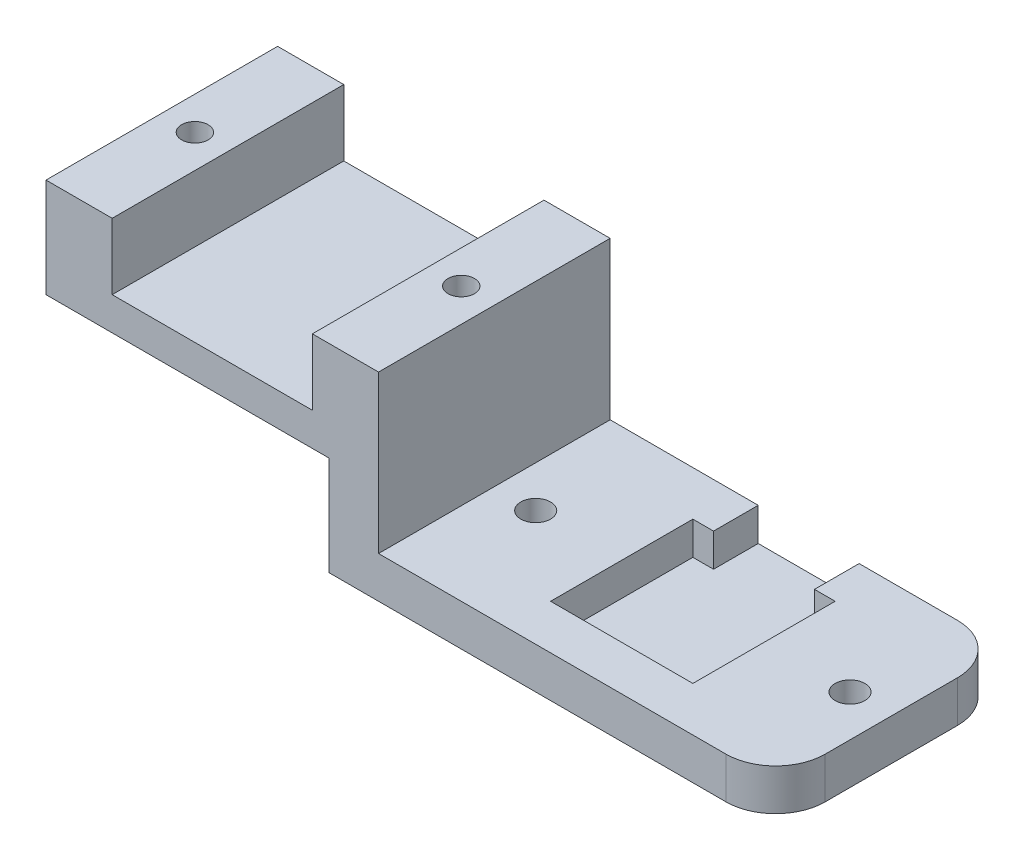
SolidWorks part; units mm, degrees
ref_plane "前视基准面" through (0, 0, 0) normal (0, 0, 1) x (1, 0, 0)
ref_plane "上视基准面" through (0, 0, 0) normal (0, 1, 0) x (1, 0, 0)
ref_plane "右视基准面" through (0, 0, 0) normal (1, 0, 0) x (0, 0, -1)
sketch "草图4" plane through (0, 0, 0) normal (0, 1, 0) x (1, 0, 0)
  line L1 (-10.05, 7) -> (10.05, 7)
  line L2 (-10.05, 7) -> (-10.05, -7)
  line L3 (-10.05, -7) -> (10.05, -7)
  line L4 (10.05, 7) -> (10.05, -7)
  line L5 (-10.05, 7) -> (10.05, -7) construction
  line L6 (-10.05, -7) -> (10.05, 7) construction
  point P0 (0, 0)
  dimension "D1" = 20.1
  dimension "D2" = 14
extrude "凸台-拉伸3" add sketch "草图4" along normal blind 6
sketch "草图5" plane through (0, 0, 7) normal (0, 0, 1) x (1, 0, 0)
  line L0 (-10.05, 6) -> (10.05, 6) construction
  line L1 (-6.05, 6) -> (6.05, 6)
  line L2 (-6.05, 6) -> (-6.05, 2)
  line L3 (-6.05, 2) -> (6.05, 2)
  line L4 (6.05, 6) -> (6.05, 2)
  line L5 (0, 0) -> (0, 6) construction
  line L6 (-10.05, 0) -> (10.05, 0) construction
  dimension "D1" = 12.1
  dimension "D2" = 2
extrude "切除-拉伸1" cut sketch "草图5" against normal through all
sketch "草图6" plane through (0, 0, 0) normal (0, -1, 0) x (1, 0, 0)
  line L0 (-10.05, 7) -> (10.05, 7) construction
  line L1 (7.05, 7) -> (10.05, 7)
  line L2 (7.05, 7) -> (7.05, -7)
  line L3 (7.05, -7) -> (10.05, -7)
  line L4 (10.05, 7) -> (10.05, -7)
  dimension "D1" = 3
extrude "凸台-拉伸4" add sketch "草图6" along normal blind 6
sketch "草图7" plane through (0, 0, -7) normal (0, 0, -1) x (-1, 0, 0)
  line L0 (-7.05, -6) -> (0, 0)
  line L1 (-7.05, 0) -> (-7.05, -6)
  line L2 (0, 0) -> (-7.05, 0)
extrude "凸台-拉伸5" add sketch "草图7" along normal blind 2 from offset 6 offset against normal yes
sketch "草图8" plane through (10.05, 0, 0) normal (1, 0, 0) x (0, 0, -1)
  line L0 (7, 6) -> (7, -6) construction
  line L1 (-7, -6) -> (7, -6)
  line L2 (-7, -6) -> (-7, -3.5)
  line L3 (-7, -3.5) -> (7, -3.5)
  line L4 (7, -6) -> (7, -3.5)
  dimension "D1" = 2.5
extrude "凸台-拉伸6" add sketch "草图8" along normal blind 24
sketch "草图9" plane through (0, -3.5, 0) normal (0, 1, 0) x (1, 0, 0)
  line L0 (22.05, 7) -> (22.05, 0) construction
  line L2 (17.75, 4.3) -> (17.75, -4.3)
  line L3 (17.75, -4.3) -> (26.35, -4.3)
  line L4 (26.35, 4.3) -> (26.35, -4.3)
  line L5 (17.75, 4.3) -> (26.35, -4.3) construction
  line L6 (17.75, -4.3) -> (26.35, 4.3) construction
  line L7 (34.05, 7) -> (10.05, 7) construction
  line L8 (34.05, 0) -> (22.05, 0) construction
  line L9 (34.05, 7) -> (34.05, -7) construction
  line L10 (17.75, 4.3) -> (19, 4.3)
  line L11 (19, 4.3) -> (19, 7)
  line L12 (19, 7) -> (25.1, 7)
  line L13 (25.1, 7) -> (25.1, 4.3)
  line L14 (25.1, 4.3) -> (26.35, 4.3)
  point P0 (22.05, 0)
  dimension "D1" = 6.1
  dimension "D2" = 8.6
extrude "切除-拉伸2" cut sketch "草图9" against normal offset from surface (2 mm away) 0.5 up to face at (16.05, -6, -0.6667)
sketch "草图10" plane through (0, -3.5, 0) normal (0, 1, 0) x (1, 0, 0)
  line L0 (0, 0) -> (12.55, 0) construction
  line L1 (0, 0) -> (31.55, 0) construction
  line L2 (34.05, 7) -> (34.05, -7) construction
  line L3 (10.05, -7) -> (10.05, 7) construction
  circle A0 centre (12.55, 0) radius 0.9
  circle A1 centre (31.55, 0) radius 0.9
  dimension "D3" = 1.8
  dimension "D1" = 2.5
  dimension "D2" = 2.5
extrude "切除-拉伸3" cut sketch "草图10" against normal through all
fillet "圆角1" radius 3 2 edges at (34.05, -4.75, -7) (34.05, -4.75, 7)
hole_wizard "M2 螺纹孔的螺纹孔钻头2" positions "3D草图4" profile "草图13" hole size "M2" standard "GB"
sketch3d "3D草图4"
  line L3 (-6.05, 6, -7) -> (-10.05, 6, -7) construction
  line L4 (-10.05, 6, -7) -> (-10.05, 6, 7) construction
  line L5 (10.05, 6, 7) -> (10.05, 6, -7) construction
  line L6 (10.05, 6, -7) -> (6.05, 6, -7) construction
  point P0 (-8.05, 6, 0)
  point P13 (8.05, 6, 0)
  dimension "D1" = 7
  dimension "D2" = 2
  dimension "D3" = 2
  dimension "D4" = 7
sketch "草图13" plane through (-8.05, 6, 0) normal (1, 0, 0) x (0, 0, 1)
  line L0 (0, 0) -> (0, 6.4807)
  line L1 (0, 6.4807) -> (0.8, 6)
  line L2 (0.8, 6) -> (0.8, 0)
  line L5 (0.8, 0) -> (0, 0)
  line L10 (0, 6.4807) -> (-0.8, 6) construction
  line L11 (0, -6.35) -> (0, 107.95) construction
  dimension "孔直径" = 1.6
  dimension "孔深度" = 6
  dimension "导头角度" = 118
